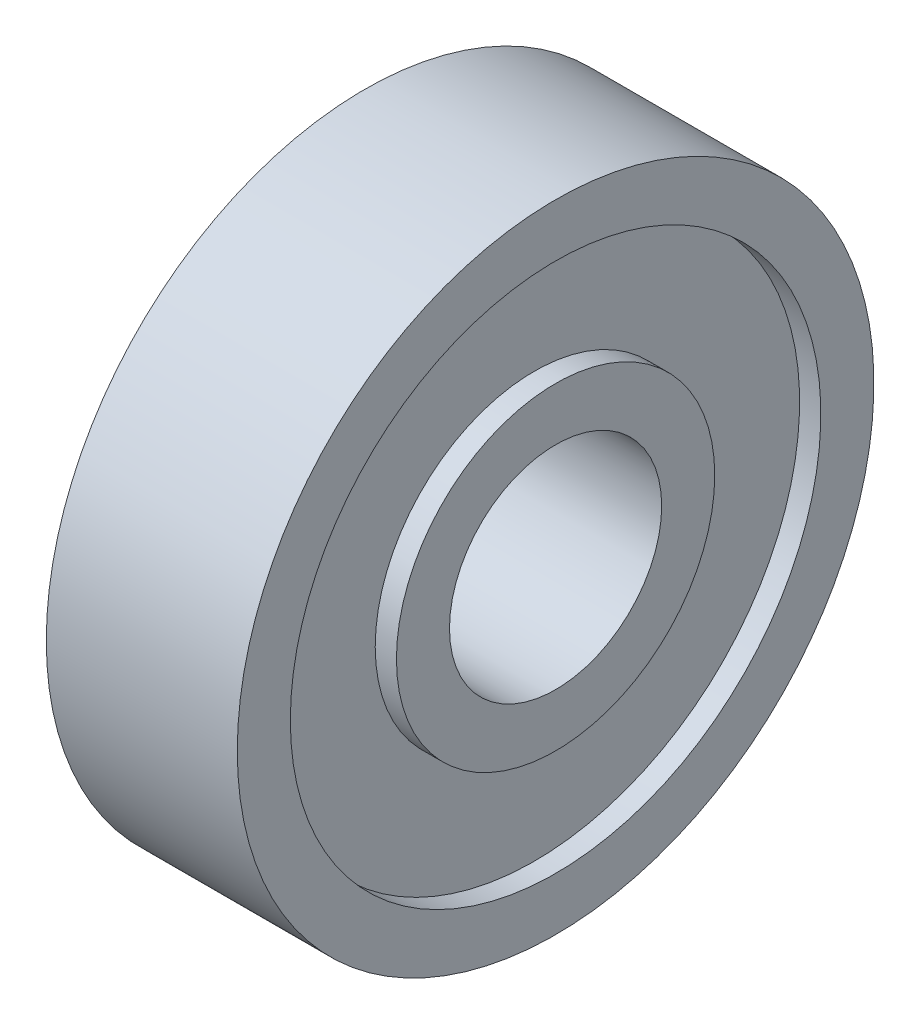
SolidWorks part; units mm, degrees
ref_plane "Front Plane" through (0, 0, 0) normal (0, 0, 1) x (1, 0, 0)
ref_plane "Top Plane" through (0, 0, 0) normal (0, 1, 0) x (1, 0, 0)
ref_plane "Right Plane" through (0, 0, 0) normal (1, 0, 0) x (0, 0, -1)
sketch "Sketch1" plane through (0, 0, 0) normal (0, 0, 1) x (1, 0, 0)
  line L0 (0, -243.0276) -> (0, 11908.3506) construction
  line L1 (-243.0276, 0) -> (11908.3506, 0) construction
  line L2 (0, 5) -> (4.5, 5)
  line L3 (4.5, 5) -> (4.5, 7.5)
  line L4 (4.5, 7.5) -> (3.5, 7.5)
  line L5 (3.5, 7.5) -> (3.5, 12.5)
  line L6 (3.5, 12.5) -> (4.5, 12.5)
  line L7 (4.5, 12.5) -> (4.5, 15)
  line L8 (4.5, 15) -> (0, 15)
  line L9 (0, 15) -> (0, 5)
  dimension "D1" = 10
  dimension "D2" = 9
  dimension "D3" = 30
  dimension "D4" = 1
  dimension "D5" = 5
revolve "Revolve1" add sketch "Sketch1" angle 360 about L1
mirror "Mirror1" of "Revolve1"
